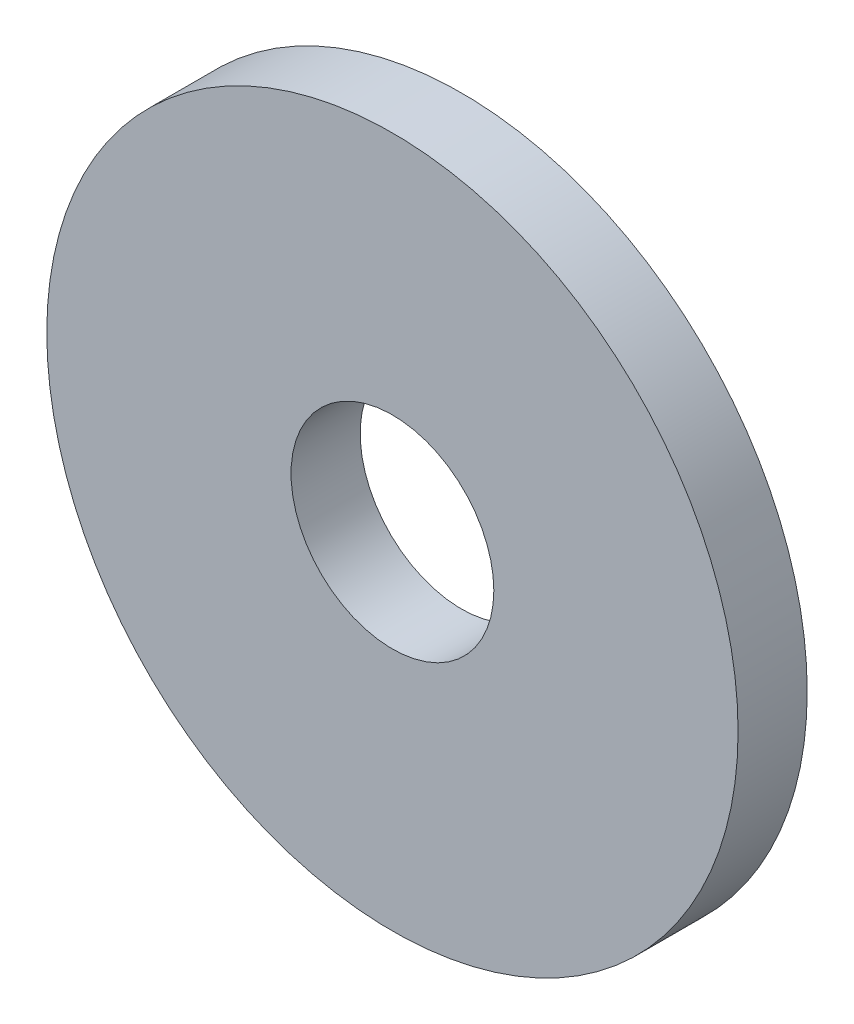
SolidWorks part; units mm, degrees
material "AISI 316 Нержавеющая сталь, лист (SS)"
ref_plane "Спереди" through (0, 0, 0) normal (0, 0, 1) x (1, 0, 0)
ref_plane "Сверху" through (0, 0, 0) normal (0, 1, 0) x (1, 0, 0)
ref_plane "Справа" through (0, 0, 0) normal (1, 0, 0) x (0, 0, -1)
sketch "Эскиз1" plane through (0, 0, 0) normal (0, 0, 1) x (1, 0, 0)
  circle A0 centre (0, 0) radius 4.4
  circle A1 centre (0, 0) radius 15
  dimension "D1" = 8.8
  dimension "D2" = 30
extrude "Бобышка-Вытянуть1" add sketch "Эскиз1" along normal blind 3
